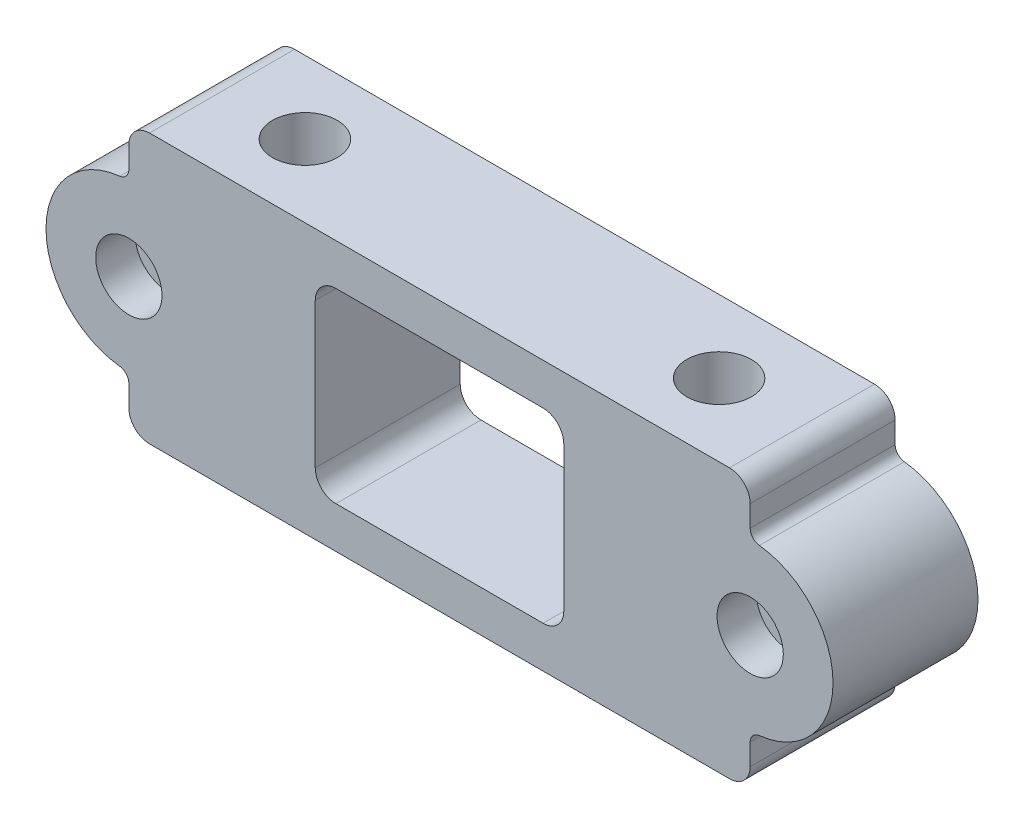
SolidWorks part; units mm, degrees
material "6061-T6 (SS)"
ref_plane "X-Y Datum" through (0, 0, 0) normal (0, 0, 1) x (1, 0, 0)
ref_plane "X-Z Datum" through (0, 0, 0) normal (0, 1, 0) x (1, 0, 0)
ref_plane "Y-Z Datum" through (0, 0, 0) normal (1, 0, 0) x (0, 0, -1)
other "Center of Mass"
other "Graphic1"
other "Graphic (Closed) -1"
other "Graphic2"
other "Graphic (Closed) -2"
other "Graphic3"
other "Graphic (Closed) -3"
sketch "Sketch1" plane through (0, 0, 0) normal (0, 1, 0) x (1, 0, 0)
  line L0 (101.6, 8.89) -> (76.2, 8.89) construction
  line L1 (101.6, 17.78) -> (0, 17.78)
  line L2 (101.6, 17.78) -> (101.6, 0)
  line L3 (101.6, 0) -> (0, 0)
  line L5 (0, 31.6293) -> (0, -17.6841) construction
  line L6 (0, 17.78) -> (0, 0)
  line L7 (76.2, 8.89) -> (25.4, 8.89) construction
  line L8 (25.4, 8.89) -> (0, 8.89) construction
  circle A0 centre (76.2, 8.89) radius 3.9688
  circle A1 centre (25.4, 8.89) radius 3.9687
  point P12 (50.8, 8.89)
  point P13 (50.8, 17.78)
  dimension "D3" = 7.9375
  dimension "D1" = 101.6
  dimension "D2" = 17.78
  dimension "D4" = 50.8
extrude "Boss-Extrude1" add sketch "Sketch1" against normal blind 33.02
sketch "Sketch2" plane through (0, 0, 0) normal (0, 0, 1) x (1, 0, 0)
  line L4 (0, -33.02) -> (0, 0) construction
  line L5 (0, -33.02) -> (101.6, -33.02) construction
  line L8 (101.6, -33.02) -> (101.6, 0) construction
  circle A0 centre (88.9, -16.51) radius 2.4892
  circle A1 centre (12.7, -16.51) radius 2.4892
  dimension "D3" = 4.9784
  dimension "D1" = 12.7
  dimension "D5" = 16.51
  dimension "D6" = 12.7
  dimension "D2" = 16.51
extrude "Cut-Extrude1" cut sketch "Sketch2" against normal up to surface (17.78 mm away) up to face at (50.8, -16.51, -17.78)
sketch "Sketch3" plane through (0, 0, 0) normal (0, 0, 1) x (1, 0, 0)
  circle A0 centre (88.9, -16.51) radius 4.064
  circle A3 centre (12.7, -16.51) radius 4.064
  circle A4 centre (12.7, -16.51) radius 2.4892 construction
  dimension "D1" = 8.128
extrude "Cut-Extrude2" cut sketch "Sketch3" against normal blind 4.826
ref_plane "Plane1" through (0, -16.51, 0) normal (0, 1, 0) x (1, 0, 0)
ref_plane "Plane2" through (0, -16.51, 0) normal (0, 1, 0) x (1, 0, 0)
sketch "Sketch5" plane through (0, 0, 0) normal (0, 0, 1) x (1, 0, 0)
  line L8 (0, -33.02) -> (101.6, -33.02) construction
  line L18 (0, -33.02) -> (0, 0) construction
  line L19 (50.8, 0) -> (50.8, -33.02) construction
  line L20 (0, 0) -> (101.6, 0) construction
  line B0 (12.7, -5.1508) -> (12.7, 0)
  line B1 (0, 0) -> (12.7, 0)
  line B2 (0, -33.02) -> (0, 0)
  line B3 (12.7, -33.02) -> (0, -33.02)
  line B4 (12.7, -27.8692) -> (12.7, -33.02)
  arc B5 (12.7, -5.1508) -> (11.5711, -6.4129) centre (11.43, -5.1508) cw
  arc B6 (12.7, -27.8692) -> (11.5711, -26.6071) centre (11.43, -27.8692) ccw
  arc B7 (11.5711, -26.6071) -> (11.5711, -6.4129) centre (12.7, -16.51) cw
  line B8 (88.9, -5.1508) -> (88.9, 0)
  line B9 (101.6, 0) -> (88.9, 0)
  line B10 (101.6, -33.02) -> (101.6, 0)
  line B11 (88.9, -33.02) -> (101.6, -33.02)
  line B12 (88.9, -27.8692) -> (88.9, -33.02)
  arc B13 (88.9, -5.1508) -> (90.0289, -6.4129) centre (90.17, -5.1508) ccw
  arc B14 (88.9, -27.8692) -> (90.0289, -26.6071) centre (90.17, -27.8692) cw
  arc B15 (90.0289, -26.6071) -> (90.0289, -6.4129) centre (88.9, -16.51) ccw
sketch_block_instance "Block2-1"
sketch_block "Block2"
sketch_block_instance "Block2-2"
extrude "Cut-Extrude3" cut sketch "Sketch5" against normal through all
fillet "Fillet1" radius 2.54 4 edges at (12.7, 0, -8.89) (88.9, 0, -8.89) (88.9, -33.02, -8.89) (12.7, -33.02, -8.89)
ref_point "Point1"
ref_point "Point2"
sketch "Sketch6" plane through (0, 0, 0) normal (0, 0, 1) x (1, 0, 0)
  line L0 (50.8, 0) -> (50.8, -33.02) construction
  line L1 (15.24, 0) -> (86.36, 0) construction
  line L2 (15.24, -33.02) -> (86.36, -33.02) construction
  line L4 (38.1, -27.94) -> (63.5, -27.94)
  line L5 (35.56, -25.4) -> (35.56, -7.62)
  line L6 (38.1, -5.08) -> (63.5, -5.08)
  line L7 (66.04, -25.4) -> (66.04, -7.62)
  line L8 (35.56, -27.94) -> (66.04, -5.08) construction
  line L9 (35.56, -5.08) -> (66.04, -27.94) construction
  arc A0 (38.1, -27.94) -> (35.56, -25.4) centre (38.1, -25.4) cw
  arc A1 (63.5, -27.94) -> (66.04, -25.4) centre (63.5, -25.4) ccw
  arc A2 (63.5, -5.08) -> (66.04, -7.62) centre (63.5, -7.62) cw
  arc A3 (35.56, -7.62) -> (38.1, -5.08) centre (38.1, -7.62) cw
  point P6 (50.8, -16.51)
  dimension "D3" = 2.54
  dimension "D1" = 30.48
  dimension "D2" = 22.86
extrude "Cut-Extrude4" cut sketch "Sketch6" against normal through all
